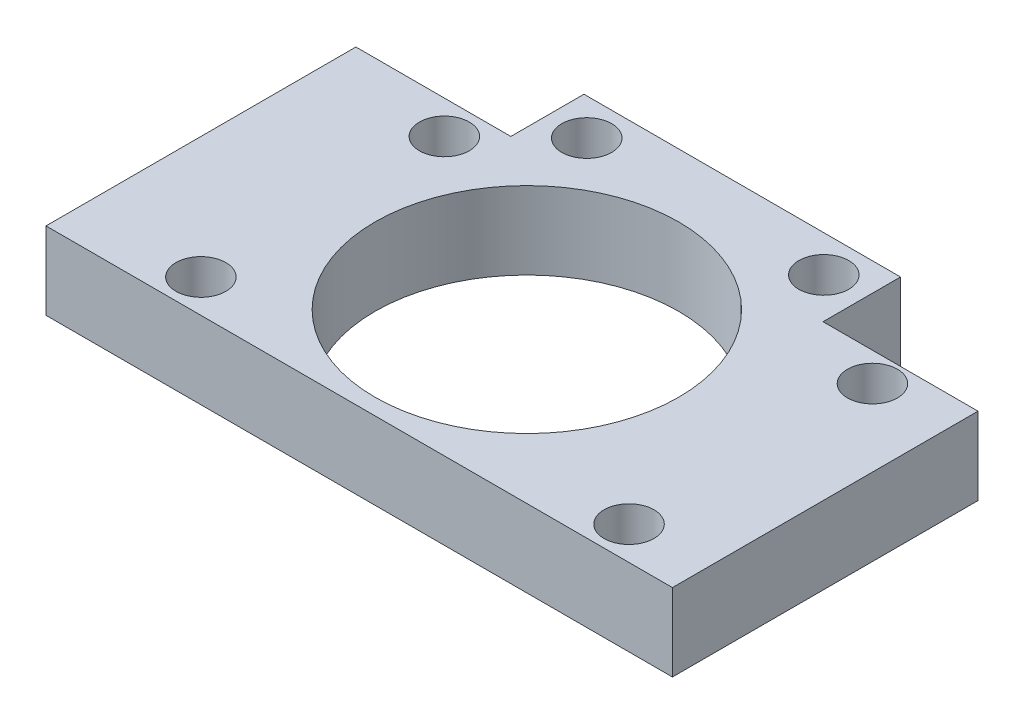
SolidWorks part; units mm, degrees
ref_plane "Alzado" through (0, 0, 0) normal (0, 0, 1) x (1, 0, 0)
ref_plane "Planta" through (0, 0, 0) normal (0, 1, 0) x (1, 0, 0)
ref_plane "Vista lateral" through (0, 0, 0) normal (1, 0, 0) x (0, 0, -1)
sketch "Croquis1" plane through (0, 0, 0) normal (0, 1, 0) x (1, 0, 0)
  line L0 (-20.193, 7.1947) -> (-10.193, 7.1947)
  line L1 (-10.193, 7.1947) -> (-10.193, 11.9147)
  line L2 (-10.193, 11.9147) -> (10.237, 11.9147)
  line L3 (10.237, 11.9147) -> (10.237, 6.9147)
  line L4 (10.237, 6.9147) -> (20.237, 6.9147)
  line L5 (20.237, 6.9147) -> (20.237, -12.8053)
  line L6 (20.237, -12.8053) -> (-20.193, -12.8053)
  line L7 (-20.193, 7.1947) -> (-20.193, -12.8053)
  line L8 (0, 14.5007) -> (0, -18.4313) construction
  line L9 (-10.193, 11.9147) -> (-0.8562, 11.9147)
  line L10 (0, 7.8347) -> (0, 11.9147)
  line L11 (0, -11.7653) -> (0, -15.8453)
  line L12 (-10.7299, 5.0497) -> (13.6801, 5.0497)
  line L13 (-12.3399, 3.4397) -> (-12.3399, -9.0503)
  line L14 (15.2901, 3.4397) -> (15.2901, -9.0503)
  line L15 (-12.3399, 6.6597) -> (-12.3399, 7.1947)
  line L16 (-10.7299, 5.0497) -> (9.8124, 5.0497)
  line L17 (-6.0435, 9.5535) -> (6.0355, 9.5535)
  circle A0 centre (0, -1.9653) radius 9.8
  circle A1 centre (-12.3399, 5.0497) radius 1.61
  circle A2 centre (-12.3399, -10.6605) radius 1.6102
  circle A3 centre (15.2901, 5.0497) radius 1.61
  circle A4 centre (15.2901, -10.6606) radius 1.6103
  circle A5 centre (-7.6538, 9.5535) radius 1.6103
  circle A6 centre (7.6458, 9.5535) radius 1.6103
  dimension "D6" = 19.6
  dimension "D13" = 3.22
  dimension "D14" = 3.22
  dimension "D15" = 3.2204
  dimension "D16" = 3.2206
  dimension "D18" = 12.0789
  dimension "D1" = 40.43
  dimension "D2" = 10
  dimension "D3" = 10
  dimension "D4" = 20
  dimension "D5" = 19.72
  dimension "D7" = 5
  dimension "D8" = 4.08
  dimension "3.16" = 4.08
  dimension "D9" = 4.72
  dimension "D10" = 24.41
  dimension "D11" = 12.49
  dimension "D12" = 12.49
  dimension "D17" = 0.535
extrude "Saliente-Extruir2" add sketch "Croquis1" along normal mid plane 5
sketch "Croquis3" plane through (0, 2.5, 0) normal (0, 1, 0) x (1, 0, 0)
  circle A0 centre (-12.3399, 5.0497) radius 1.61 construction
  circle A1 centre (-12.3399, 5.0497) radius 1.61
sketch "Croquis4" plane through (0, 2.5, 0) normal (0, 1, 0) x (1, 0, 0)
  circle A0 centre (15.2901, 5.0497) radius 1.61 construction
  circle A1 centre (15.2901, 5.0497) radius 1.61
sketch "Croquis5" plane through (0, 0, 0) normal (0, 1, 0) x (1, 0, 0)
  circle A0 centre (-12.3399, -10.6605) radius 1.6102 construction
  circle A1 centre (-12.3399, -10.6605) radius 1.6102
sketch "Croquis6" plane through (0, 0, 0) normal (0, 1, 0) x (1, 0, 0)
  circle A0 centre (15.2901, -10.6606) radius 1.6103 construction
  circle A1 centre (15.2901, -10.6606) radius 1.6103
ref_plane "Plano1" through (15, 0, 0) normal (1, 0, 0) x (0, 0, -1)
ref_plane "Plano2" through (-12, 0, 0) normal (1, 0, 0) x (0, 0, -1)
sketch "Croquis14" plane through (0, 2.5, 0) normal (0, 1, 0) x (1, 0, 0)
  circle A0 centre (-12.3399, 5.0497) radius 1.61 construction
  circle A1 centre (-12.3399, 5.0497) radius 1.61
curve "Hélice/Espiral7" pitch 0.7 height 8.4 turns 12
sketch "Croquis15" plane through (0, 2.5, 0) normal (0, 1, 0) x (1, 0, 0)
  circle A0 centre (15.2901, 5.0497) radius 1.61 construction
  circle A1 centre (15.2901, 5.0497) radius 1.61
curve "Hélice/Espiral8" pitch 0.7 height 8.4 turns 12
sketch "Croquis16" plane through (0, 2.5, 0) normal (0, 1, 0) x (1, 0, 0)
  circle A0 centre (15.2901, -10.6606) radius 1.6103 construction
  circle A1 centre (15.2901, -10.6606) radius 1.6103
curve "Hélice/Espiral9" pitch 0.7 height 8.4 turns 12
sketch "Croquis17" plane through (0, 2.5, 0) normal (0, 1, 0) x (1, 0, 0)
  circle A0 centre (-12.3399, -10.6605) radius 1.6102 construction
  circle A1 centre (-12.3399, -10.6605) radius 1.6102
curve "Hélice/Espiral10" pitch 0.7 height 8.4 turns 12
sketch "Croquis19" plane through (15, 0, 0) normal (1, 0, 0) x (0, 0, -1)
  line L1 (-13.1424, 4) -> (-12.2764, 3.5)
  line L2 (-12.2764, 3.5) -> (-12.2764, 4.5)
  line L3 (-12.2764, 4.5) -> (-13.1424, 4)
  line L4 (2.583, 4) -> (3.449, 3.5)
  line L5 (3.449, 3.5) -> (3.449, 4.5)
  line L6 (3.449, 4.5) -> (2.583, 4)
  circle A0 centre (-12.5651, 4) radius 0.2887 construction
  circle A1 centre (3.1603, 4) radius 0.2887 construction
  point P7 (0, 0)
  point P12 (0, 0)
  dimension "D1" = 1
  dimension "D2" = 12.2764
  dimension "D3" = 4
  dimension "D4" = 1
  dimension "D5" = 4
  dimension "D6" = 3.449
sketch "Croquis20" plane through (15, 0, 0) normal (1, 0, 0) x (0, 0, -1)
